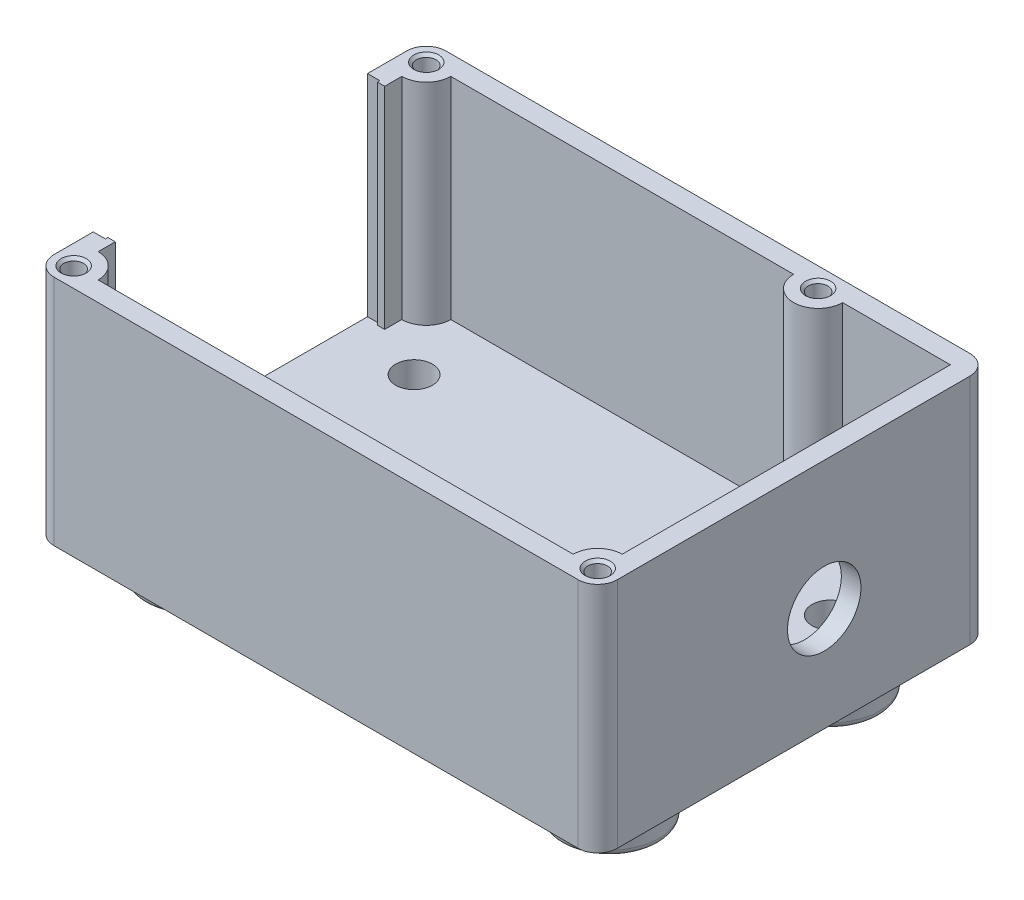
SolidWorks part; units mm, degrees
material "201.0-T7 Insulated Mold Casting (SS)"
ref_plane "Front Plane" through (0, 0, 0) normal (0, 0, 1) x (1, 0, 0)
ref_plane "Top Plane" through (0, 0, 0) normal (0, 1, 0) x (1, 0, 0)
ref_plane "Right Plane" through (0, 0, 0) normal (1, 0, 0) x (0, 0, -1)
sketch "Sketch1" plane through (0, 0, 0) normal (0, 1, 0) x (1, 0, 0)
  line L0 (0, 0) -> (-14, 0) construction
  line L1 (-14, 16) -> (32, 16)
  line L2 (-14, 16) -> (-14, -16)
  line L3 (-14, -16) -> (32, -16)
  line L4 (32, 16) -> (32, -16)
  dimension "D1" = 32
  dimension "D2" = 46
  dimension "D3" = 14
extrude "Boss-Extrude1" add sketch "Sketch1" against normal blind 19
hole_wizard "M2x0.4 Tapped Hole1" positions "Sketch3" profile "Sketch2" tap size "M2x0.4" standard "ANSI Metric"
sketch "Sketch3" plane through (0, 0, 0) normal (0, 1, 0) x (1, 0, 0)
  line L0 (-12.4, 14.4) -> (19.6, 14.4) construction
  line L2 (30.4, -14.4) -> (-12.4, -14.4) construction
  line L4 (-14, 16) -> (-14, -16) construction
  line L5 (32, 16) -> (-14, 16) construction
  line L8 (-14, -16) -> (32, -16) construction
  line L9 (32, -16) -> (32, 16) construction
  line L10 (-12.4, 14.4) -> (-12.4, -14.4) construction
  point P0 (-12.4, 14.4)
  point P2 (19.6, 14.4)
  point P4 (30.4, -14.4)
  point P6 (-12.4, -14.4)
  dimension "D1" = 1.6
  dimension "D2" = 1.6
  dimension "D3" = 1.6
  dimension "D4" = 1.6
  dimension "D5" = 32
sketch "Sketch2" plane through (-12.4, 0, -14.4) normal (1, 0, 0) x (0, 0, 1)
  line L0 (0, 0) -> (0, 6.4807)
  line L1 (0, 6.4807) -> (0.8, 6)
  line L2 (0.8, 6) -> (0.8, 0.225)
  line L3 (0.8, 0.225) -> (1.025, 0)
  line L5 (1.025, 0) -> (0, 0)
  line L6 (-0.8, 0.225) -> (-1.025, 0) construction
  line L10 (0, 6.4807) -> (-0.8, 6) construction
  line L11 (0, -6.35) -> (0, 107.95) construction
  dimension "Tap Drill Dia." = 1.6
  dimension "Tap Drill Depth" = 6
  dimension "Near C'Sink Dia." = 2.05
  dimension "Near C'Sink Angle" = 90
  dimension "Drill Angle" = 118
sketch "Sketch4" plane through (0, -19, 0) normal (0, -1, 0) x (-1, 0, 0)
  line L0 (-12, -5.5) -> (-12, 5.5) construction
  line L1 (0, 0) -> (-12, 0) construction
  circle A0 centre (0, 0) radius 4
  circle A1 centre (-12, -5.5) radius 3.5
  circle A2 centre (-12, 5.5) radius 3.5
  dimension "D1" = 8
  dimension "D4" = 7
  dimension "D2" = 11
  dimension "D3" = 12
extrude "Boss-Extrude2" [suppressed] add sketch "Sketch4" along normal blind 2
sketch "Sketch5" plane through (0, -19, 0) normal (0, 1, 0) x (1, 0, 0)
  line L0 (32, -16) -> (32, 16) construction
  line L1 (19, 0) -> (32, 0)
  line L2 (19, 0) -> (19, -12)
  line L3 (19, -12) -> (32, -12)
  line L4 (32, 0) -> (32, -12)
  line L6 (-14, -16) -> (32, -16) construction
  dimension "D1" = 13
  dimension "D2" = 12
  dimension "D3" = 4
extrude "Boss-Extrude4" [suppressed] add sketch "Sketch5" against normal blind 2
fillet "Fillet1" radius 1.6 4 edges at (-14, -9.5, -16) (32, -9.5, -16) (32, -9.5, 16) (-14, -9.5, 16)
fillet "Fillet2" [suppressed] radius 1.6
fillet "Fillet3" [suppressed] radius 0.2
sketch "Sketch8" plane through (0, 0, 0) normal (0, 1, 0) x (1, 0, 0)
  line L0 (30.4, 16) -> (-12.4, 16) construction
  line L1 (-10.4, 14.4) -> (17.6, 14.4)
  line L2 (-12.4, 12.4) -> (-12.4, -12.4)
  line L3 (-10.4, -14.4) -> (28.4, -14.4)
  line L4 (30.4, 14.4) -> (30.4, -12.4)
  line L5 (-12.4, 14.4) -> (30.4, -14.4) construction
  line L6 (-12.4, -14.4) -> (30.4, 14.4) construction
  line L7 (-12.4, -16) -> (30.4, -16) construction
  line L8 (32, -14.4) -> (32, 14.4) construction
  line L9 (-14, 14.4) -> (-14, -14.4) construction
  line L10 (21.6, 14.4) -> (30.4, 14.4)
  arc A0 (-12.4, 12.4) -> (-10.4, 14.4) centre (-12.4, 14.4) ccw
  arc A1 (17.6, 14.4) -> (21.6, 14.4) centre (19.6, 14.4) ccw
  arc A2 (30.4, -12.4) -> (28.4, -14.4) centre (30.4, -14.4) ccw
  arc A3 (-10.4, -14.4) -> (-12.4, -12.4) centre (-12.4, -14.4) ccw
  circle A4 centre (-12.4, 14.4) radius 0.8 construction
  circle A5 centre (30.4, -14.4) radius 0.8 construction
  circle A6 centre (-12.4, -14.4) radius 0.8 construction
  point P0 (9, 0)
  dimension "D5" = 4
  dimension "D1" = 1.6
  dimension "D2" = 1.6
  dimension "D3" = 1.6
  dimension "D4" = 1.6
extrude "Cut-Extrude3" cut sketch "Sketch8" against normal offset from surface (17.2 mm away) 1.8 up to face at (9, -19, 0)
sketch "Sketch6" plane through (0, 0, 0) normal (0, 1, 0) x (1, 0, 0)
  line L0 (-14, 14.4) -> (-14, -14.4) construction
  line L1 (-12, 11) -> (-14, 11)
  line L2 (-12, 11) -> (-12, -11)
  line L3 (-12, -11) -> (-14, -11)
  line L4 (-14, 11) -> (-14, -11)
  line L5 (-12, 11) -> (-14, -11) construction
  line L6 (-12, -11) -> (-14, 11) construction
  line L7 (0, 0) -> (-13, 0) construction
  point P0 (-13, 0)
  dimension "D1" = 2
  dimension "D2" = 22
extrude "Cut-Extrude1" cut sketch "Sketch6" against normal offset from surface (17.2 mm away) 1.8 up to face at (9, -19, 0)
sketch "Sketch7" plane through (0, 0, 0) normal (0, 1, 0) x (1, 0, 0)
  line L0 (-14, -11) -> (-14, -14.4) construction
  line L1 (-13, 11.2) -> (-14, 11.2)
  line L2 (-13, 11.2) -> (-13, -11.2)
  line L3 (-13, -11.2) -> (-14, -11.2)
  line L4 (-14, 11.2) -> (-14, -11.2)
  line L5 (-13, 11.2) -> (-14, -11.2) construction
  line L6 (-13, -11.2) -> (-14, 11.2) construction
  line L7 (0, 0) -> (-13.5, 0) construction
  point P0 (-13.5, 0)
  dimension "D1" = 22.4
  dimension "D2" = 1
extrude "Cut-Extrude2" cut sketch "Sketch7" against normal up to surface (17.2 mm away) up to face at (2.3396, -17.2, -1.1396)
sketch "Sketch9" plane through (32, 0, 0) normal (1, 0, 0) x (0, 0, -1)
  line L0 (-14.4, 0) -> (14.4, 0) construction
  line L1 (16, 0) -> (16, -19) construction
  circle A0 centre (2.5, -10.5) radius 3
  dimension "D2" = 6
  dimension "D3" = 13.5
  dimension "D1" = 10.5
extrude "Cut-Extrude4" cut sketch "Sketch9" against normal through all
sketch "Sketch10" plane through (0, -19, 0) normal (0, -1, 0) x (1, 0, 0)
  line L0 (32, 14.4) -> (32, -14.4) construction
  line L1 (-12.4, 16) -> (30.4, 16) construction
  line L2 (-14, 0) -> (32, 0) construction
  line L3 (-14, -14.4) -> (-14, 14.4) construction
  line L4 (9, 16) -> (9, -16) construction
  line L5 (30.4, -16) -> (-12.4, -16) construction
  circle A0 centre (26, 9) radius 1.5
  circle A1 centre (26, -9) radius 1.5
  circle A2 centre (-8, -9) radius 1.5
  circle A3 centre (-8, 9) radius 1.5
  dimension "D1" = 3
  dimension "D2" = 6
  dimension "D3" = 7
extrude "Cut-Extrude5" cut sketch "Sketch10" against normal blind 10
sketch "Sketch11" plane through (32, 0, 0) normal (1, 0, 0) x (0, 0, -1)
  line L0 (2.5, -22.5) -> (2.5, -19) construction
  line L1 (-14.4, -19) -> (14.4, -19) construction
  circle A0 centre (2.5, -10.5) radius 12
  dimension "D1" = 24
  dimension "D2" = 3.5
sketch "Sketch12" plane through (0, -19, 0) normal (0, -1, 0) x (1, 0, 0)
  line L0 (-14, 0) -> (32, 0) construction
  line L1 (-14, -14.4) -> (-14, 14.4) construction
  line L2 (32, -14.5) -> (32, 9.5) construction
  line L3 (9, 16) -> (9, -16) construction
  line L4 (-12.4, 16) -> (30.4, 16) construction
  line L5 (30.4, -16) -> (-12.4, -16) construction
  circle A0 centre (-8, 9) radius 4
  circle A1 centre (-8, 9) radius 1.5
  circle A2 centre (26, 9) radius 1.5
  circle A3 centre (26, 9) radius 4
  circle A4 centre (26, -9) radius 1.5
  circle A5 centre (26, -9) radius 4
  circle A6 centre (-8, -9) radius 1.5
  circle A7 centre (-8, -9) radius 4
  dimension "D1" = 8
  dimension "D2" = 3
extrude "Boss-Extrude5" add sketch "Sketch12" along normal blind 3.5
fillet "Fillet4" radius 0.5 4 edges at (26, -22.5, -13) (26, -22.5, 13) (-8, -22.5, 5) (-8, -22.5, -5)
